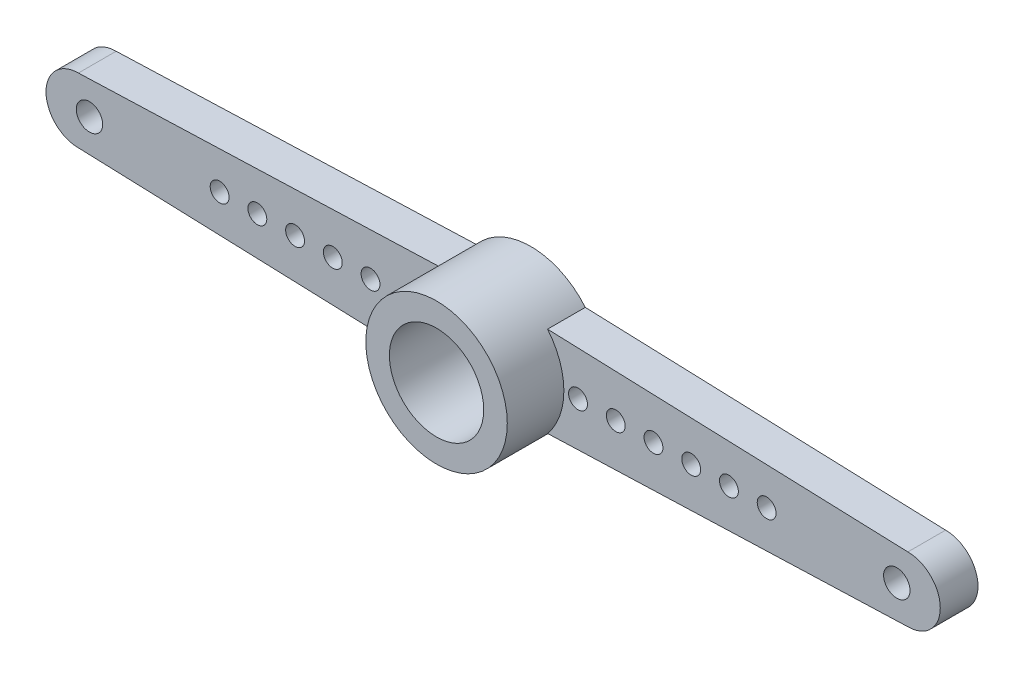
SolidWorks part; units mm, degrees
ref_plane "Спереди" through (0, 0, 0) normal (0, 0, 1) x (1, 0, 0)
ref_plane "Сверху" through (0, 0, 0) normal (0, 1, 0) x (1, 0, 0)
ref_plane "Справа" through (0, 0, 0) normal (1, 0, 0) x (0, 0, -1)
sketch "Эскиз1" plane through (0, 0, 0) normal (0, 0, 1) x (1, 0, 0)
  line L0 (0, 0) -> (-14, 0)
  line L1 (-21.9862, 1.7183) -> (0, 2.4974)
  line L2 (-21.9862, -1.7183) -> (0, -2.4974)
  line L4 (21.9862, -1.7183) -> (0, -2.4974)
  line L5 (21.9862, 1.7183) -> (0, 2.4974)
  circle A0 centre (0, 0) radius 3.75
  circle A1 centre (0, 0) radius 2.5
  arc A2 (21.9862, 1.7183) -> (21.9862, -1.7183) centre (21.9862, 0) cw
  arc A3 (-21.9862, 1.7183) -> (-21.9862, -1.7183) centre (-21.9862, 0) ccw
  point P11 (-23.6, 0.3079)
  dimension "D1" = 7.5
  dimension "D2" = 5
  dimension "D4" = 23.6
  dimension "D3" = 14
extrude "Бобышка-Вытянуть3" add sketch "Эскиз1" along normal blind 2
sketch "Эскиз2" plane through (0, 0, 2) normal (0, 0, 1) x (1, 0, 0)
  circle A0 centre (0, 0) radius 3.75
  circle A1 centre (0, 0) radius 2.5
  dimension "D1" = 5
extrude "Бобышка-Вытянуть5" add sketch "Эскиз2" along normal blind 3 separate body
sketch "Эскиз3" plane through (0, 0, 2) normal (0, 0, -1) x (-1, 0, 0)
  circle A0 centre (0, 0) radius 3.75
  circle A1 centre (0, 0) radius 2.5
extrude "Бобышка-Вытянуть6" add sketch "Эскиз3" along normal blind 2
sketch "Эскиз4" plane through (0, 0, 0) normal (0, 0, -1) x (-1, 0, 0)
  line L0 (-16, 0) -> (-14.5, 0)
  line L1 (-14.5, 0) -> (-12.5, 0)
  line L2 (-12.5, 0) -> (-10.5, 0)
  line L3 (-10.5, 0) -> (-8.5, 0)
  line L4 (-8.5, 0) -> (-6.5, 0)
  line L5 (-6.5, 0) -> (-4.5, 0)
  arc A0 (-14.0708, 1.9987) -> (-14.0708, -1.9987) centre (-14, 0) ccw construction
  circle A1 centre (-14.5, 0) radius 0.5
  circle A2 centre (-12.5, 0) radius 0.5
  circle A3 centre (-10.5, 0) radius 0.5
  circle A4 centre (-8.5, 0) radius 0.5
  circle A5 centre (-6.5, 0) radius 0.5
  circle A6 centre (-4.5, 0) radius 0.5
  circle A7 centre (4.5, 0) radius 0.5
  circle A8 centre (6.5, 0) radius 0.5
  circle A9 centre (8.5, 0) radius 0.5
  circle A10 centre (10.5, 0) radius 0.5
  circle A11 centre (12.5, 0) radius 0.5
  circle A12 centre (14.5, 0) radius 0.5
  dimension "D2" = 1
  dimension "D8" = 1
  dimension "D9" = 1
  dimension "D10" = 1
  dimension "D11" = 1
  dimension "D12" = 1
  dimension "D1" = 1.5
  dimension "D3" = 2
  dimension "D4" = 2
  dimension "D5" = 2
  dimension "D6" = 2
  dimension "D7" = 2
extrude "Вырез-Вытянуть1" cut sketch "Эскиз4" against normal blind 2
sketch "Эскиз5" plane through (0, 0, 0) normal (0, 0, -1) x (-1, 0, 0)
  circle A0 centre (0, 0) radius 2.5
extrude "Бобышка-Вытянуть7" add sketch "Эскиз5" against normal blind 1
sketch "Эскиз6" plane through (0, 0, 0) normal (0, 0, -1) x (-1, 0, 0)
  circle A0 centre (0, 0) radius 2.5
  dimension "D1" = 5
extrude "Вырез-Вытянуть2" cut sketch "Эскиз6" against normal blind 0.5
sketch "Эскиз7" plane through (0, 0, 0.5) normal (0, 0, -1) x (-1, 0, 0)
  circle A0 centre (0, 0) radius 1.25
  dimension "D1" = 2.5
extrude "Вырез-Вытянуть3" cut sketch "Эскиз7" against normal blind 5
sketch "Эскиз8" plane through (0, 0, 0.5) normal (0, 0, -1) x (-1, 0, 0)
  line L0 (-2.8252, -0.1999) -> (-2.8894, -0.2509)
sketch "Sketch1" plane through (0, 0, 5) normal (0, 0, 1) x (1, 0, 0)
  line L2 (2.8855, -2.3951) -> (21.9862, -1.7183)
  line L3 (21.9862, 1.7183) -> (2.8855, 2.3951)
  line L4 (2.8855, -2.3951) -> (21.9862, -1.7183)
  line L5 (21.9862, 1.7183) -> (2.8855, 2.3951)
  arc A0 (2.8855, -2.3951) -> (2.8855, 2.3951) centre (0, 0) ccw
  arc A3 (2.8855, -2.3951) -> (2.8855, 2.3951) centre (0, 0) ccw
  arc A4 (21.9862, -1.7183) -> (21.9862, 1.7183) centre (21.9862, 0) ccw
  arc A5 (2.8855, -2.3951) -> (2.8855, 2.3951) centre (0, 0) ccw
  arc A7 (21.9862, -1.7183) -> (21.9862, 1.7183) centre (21.9862, 0) ccw
  dimension "D1" = 0
sketch "Sketch4" plane through (0, 0, 0) normal (0, 0, -1) x (-1, 0, 0)
  circle A0 centre (21.4, 0) radius 0.7
  dimension "D1" = 21.4
extrude "Cut-Extrude3" cut sketch "Sketch4" against normal blind 2
sketch "Sketch5" plane through (0, 0, 0) normal (0, 0, -1) x (-1, 0, 0)
  circle A0 centre (-21.4, 0) radius 0.7
  dimension "D1" = 21.4
extrude "Cut-Extrude4" cut sketch "Sketch5" against normal blind 2
